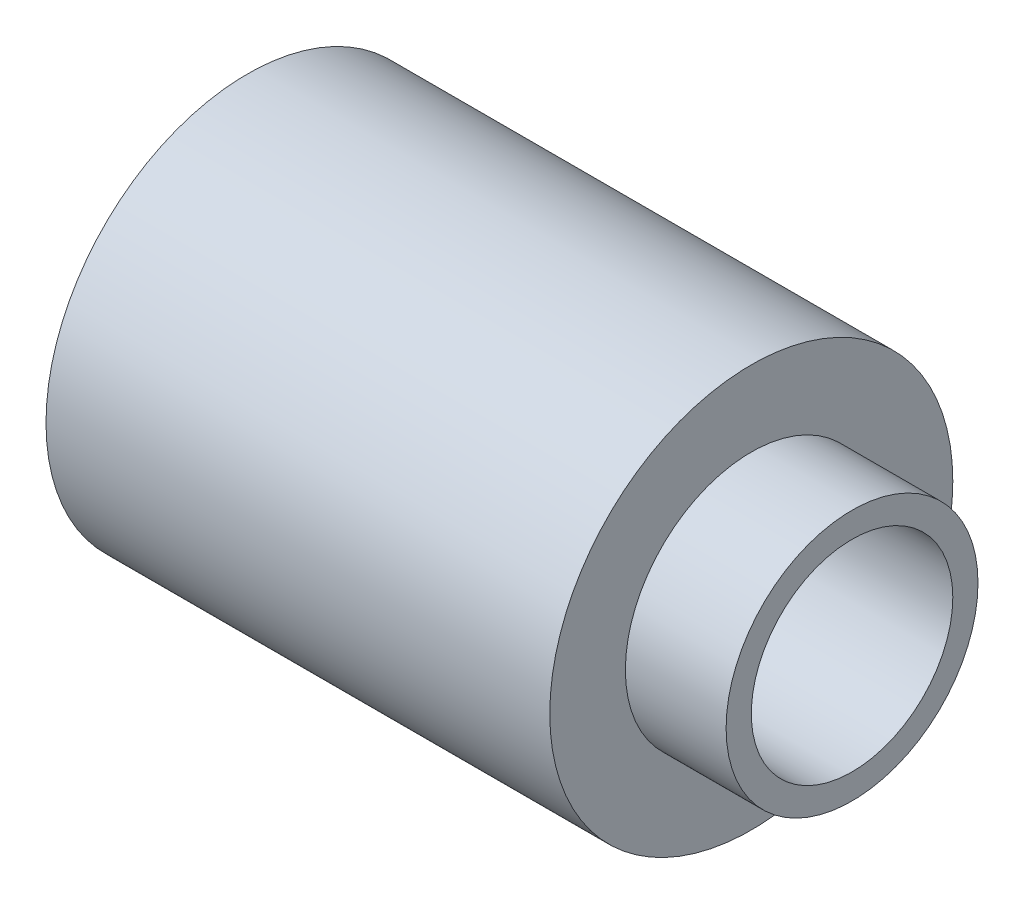
SolidWorks part; units mm, degrees
ref_plane "Front Plane" through (0, 0, 0) normal (0, 0, 1) x (1, 0, 0)
ref_plane "Top Plane" through (0, 0, 0) normal (0, 1, 0) x (1, 0, 0)
ref_plane "Right Plane" through (0, 0, 0) normal (1, 0, 0) x (0, 0, -1)
sketch "Sketch1" plane through (0, 0, 0) normal (1, 0, 0) x (0, 0, -1)
  circle A0 centre (0, 0) radius 4
  circle A1 centre (0, 0) radius 2
  dimension "D1" = 4
  dimension "D2" = 8
extrude "Boss-Extrude1" add sketch "Sketch1" along normal blind 10
sketch "Sketch2" plane through (10, 0, 0) normal (1, 0, 0) x (0, 0, -1)
  circle A0 centre (0, 0) radius 2 construction
  circle A1 centre (0, 0) radius 2
  circle A2 centre (0, 0) radius 2.5
  dimension "D1" = 0.5
extrude "Boss-Extrude2" add sketch "Sketch2" along normal blind 2
